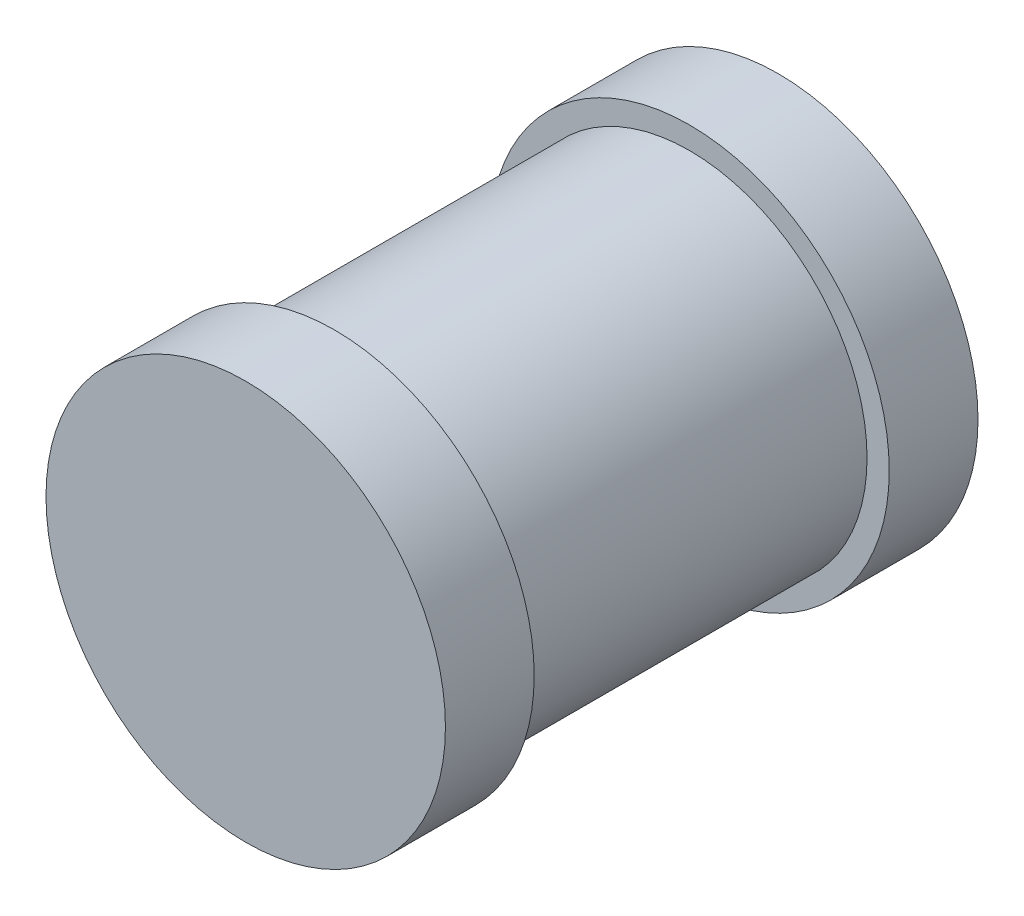
SolidWorks part; units mm, degrees
ref_plane "Front Plane" through (0, 0, 0) normal (0, 0, 1) x (1, 0, 0)
ref_plane "Top Plane" through (0, 0, 0) normal (0, 1, 0) x (1, 0, 0)
ref_plane "Right Plane" through (0, 0, 0) normal (1, 0, 0) x (0, 0, -1)
sketch "Sketch1" plane through (0, 0, 0) normal (0, 0, 1) x (1, 0, 0)
  circle A0 centre (0, 0) radius 4
  dimension "D2" = 8
extrude "Boss-Extrude3" add sketch "Sketch1" along normal blind 8
sketch "Sketch4" plane through (0, 0, 8) normal (0, 0, 1) x (1, 0, 0)
  circle A0 centre (0, 0) radius 4.5
  dimension "D1" = 9
extrude "Boss-Extrude4" add sketch "Sketch4" along normal blind 2
sketch "Sketch5" plane through (0, 0, 0) normal (0, 0, -1) x (-1, 0, 0)
  circle A0 centre (0, 0) radius 4.5
  dimension "D1" = 9
extrude "Boss-Extrude5" add sketch "Sketch5" along normal blind 2
equation "\"ค\"=48.6254"
